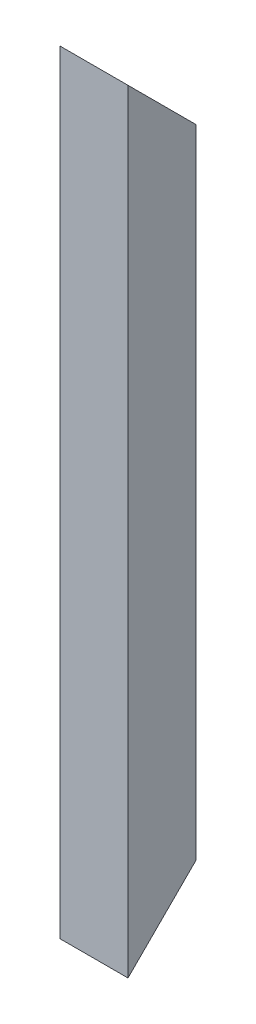
SolidWorks part; units mm, degrees
ref_plane "Спереди" through (0, 0, 0) normal (0, 0, 1) x (1, 0, 0)
ref_plane "Сверху" through (0, 0, 0) normal (0, 1, 0) x (1, 0, 0)
ref_plane "Справа" through (0, 0, 0) normal (1, 0, 0) x (0, 0, -1)
sketch "Эскиз1" plane through (0, 0, 0) normal (0, 1, 0) x (1, 0, 0)
  line L0 (0, 0) -> (0, 2)
  line L1 (0, 2) -> (20, 2)
  line L2 (20, 2) -> (20, 22)
  line L3 (20, 22) -> (22, 22)
  line L4 (22, 22) -> (22, 0)
  line L5 (22, 0) -> (0, 0)
  point P7 (0, 0)
  dimension "D1" = 2
  dimension "D2" = 20
extrude "Бобышка-Вытянуть1" add sketch "Эскиз1" along normal blind 250
sketch "Эскиз3" plane through (22, 0, 0) normal (1, 0, 0) x (0, 0, -1)
  line L0 (0, 0) -> (22, 0)
  line L1 (22, 0) -> (22, 22)
  line L2 (22, 250) -> (22, 0) construction
  line L3 (22, 22) -> (0, 0)
  line L4 (22, 250) -> (22, 228)
  line L5 (22, 228) -> (0, 250)
  line L6 (0, 250) -> (22, 250)
  dimension "D1" = 45
  dimension "D2" = 45
extrude "Вырез-Вытянуть1" cut sketch "Эскиз3" against normal blind 250
